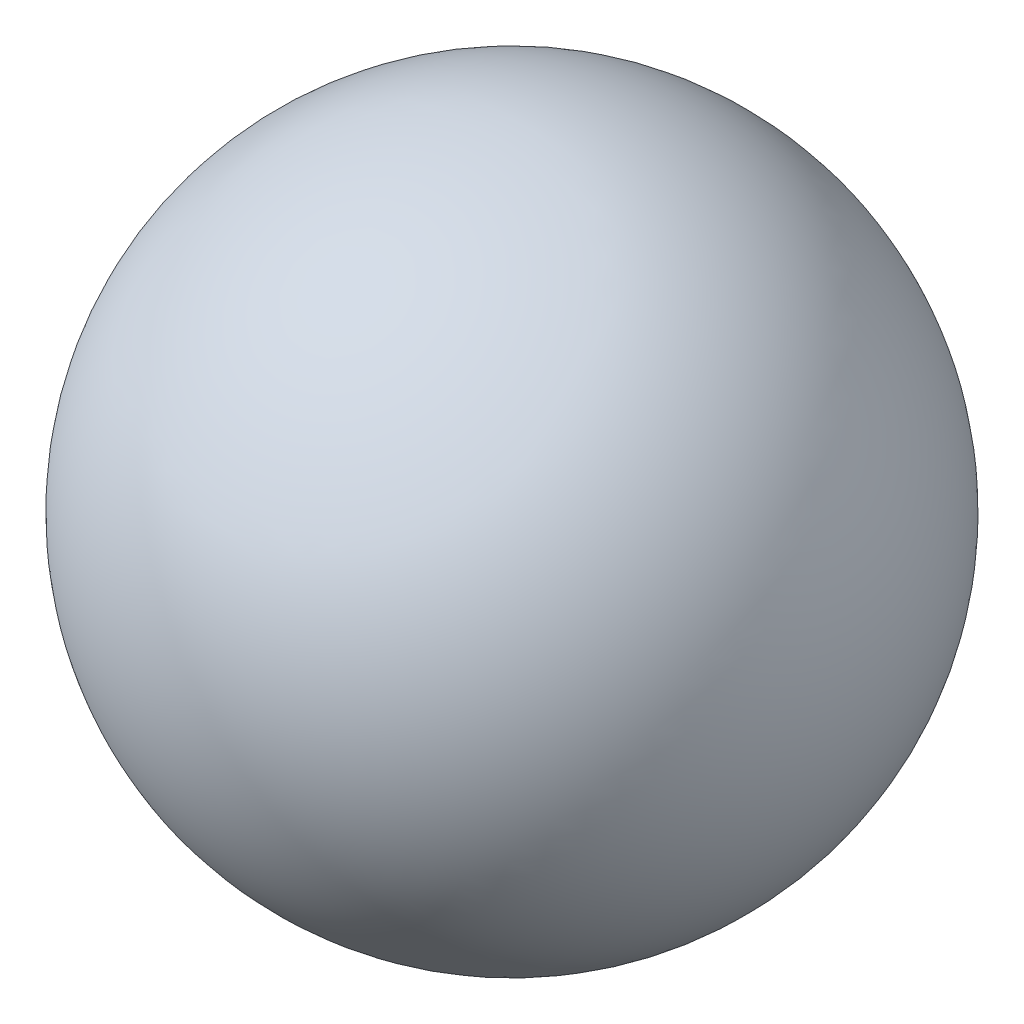
SolidWorks part; units mm, degrees
ref_plane "前视基准面" through (0, 0, 0) normal (0, 0, 1) x (1, 0, 0)
ref_plane "上视基准面" through (0, 0, 0) normal (0, 1, 0) x (1, 0, 0)
ref_plane "右视基准面" through (0, 0, 0) normal (1, 0, 0) x (0, 0, -1)
sketch "草图1" plane through (0, 0, 0) normal (0, 1, 0) x (1, 0, 0)
  line L0 (0, 22.7534) -> (0, -21.2466)
  arc A0 (0, 22.7534) -> (0, -21.2466) centre (0, 0.7534) cw
  dimension "D1" = 22
revolve "旋转1" add sketch "草图1" angle 360 about L0
